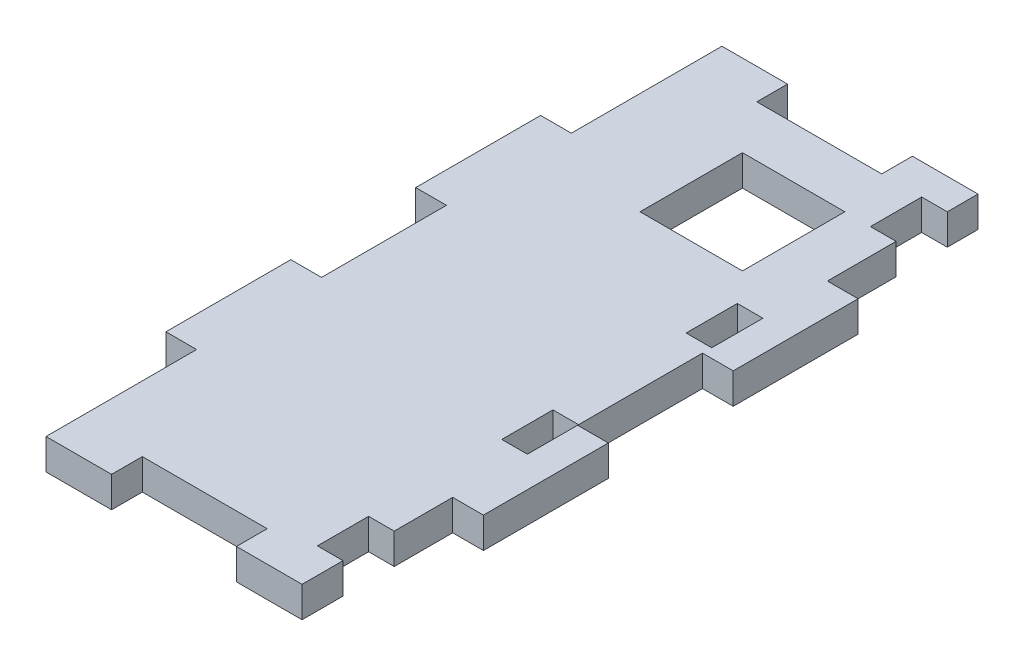
SolidWorks part; units mm, degrees
ref_plane "Front Plane" through (0, 0, 0) normal (0, 0, 1) x (1, 0, 0)
ref_plane "Top Plane" through (0, 0, 0) normal (0, 1, 0) x (1, 0, 0)
ref_plane "Right Plane" through (0, 0, 0) normal (1, 0, 0) x (0, 0, -1)
sketch "Sketch2" plane through (0, 0, 0) normal (0, 1, 0) x (1, 0, 0)
  line L0 (121, 270) -> (121, 240.585)
  line L1 (121, 240.585) -> (115, 240.585)
  line L2 (115, 240.585) -> (115, 216.195)
  line L3 (115, 216.195) -> (121, 216.195)
  line L4 (121, 216.195) -> (121, 191.805)
  line L5 (121, 191.805) -> (115, 191.805)
  line L6 (115, 191.805) -> (115, 167.415)
  line L7 (115, 167.415) -> (121, 167.415)
  line L8 (121, 167.415) -> (121, 143.025)
  line L9 (121, 143.025) -> (121, 138)
  line L10 (121, 138) -> (133.805, 138)
  line L11 (133.805, 138) -> (133.805, 144)
  line L12 (133.805, 144) -> (158.195, 144)
  line L13 (158.195, 144) -> (158.195, 138)
  line L14 (158.195, 138) -> (171, 138)
  line L15 (171, 138) -> (171, 167.415)
  line L16 (171, 167.415) -> (177, 167.415)
  line L17 (177, 167.415) -> (177, 191.805)
  line L18 (177, 191.805) -> (171, 191.805)
  line L19 (171, 191.805) -> (171, 216.195)
  line L20 (171, 216.195) -> (177, 216.195)
  line L21 (177, 216.195) -> (177, 240.585)
  line L22 (177, 240.585) -> (171, 240.585)
  line L23 (171, 240.585) -> (171, 264.975)
  line L24 (171, 264.975) -> (171, 270)
  line L25 (171, 270) -> (158.195, 270)
  line L26 (158.195, 270) -> (158.195, 264)
  line L27 (158.195, 264) -> (133.805, 264)
  line L28 (133.805, 264) -> (133.805, 270)
  line L29 (133.805, 270) -> (121, 270)
extrude "Boss-Extrude1" add sketch "Sketch2" along normal blind 6
sketch "Sketch3" plane through (0, 6, 0) normal (0, 1, 0) x (1, 0, 0)
  line L0 (171, 138) -> (171, 167.415) construction
  line L1 (141, 254) -> (161, 254)
  line L2 (141, 254) -> (141, 234)
  line L3 (141, 234) -> (161, 234)
  line L4 (161, 254) -> (161, 234)
  line L5 (158.195, 264) -> (133.805, 264) construction
  line L6 (171, 228) -> (171, 218)
  line L7 (171, 240.585) -> (171, 270) construction
  line L8 (171, 264) -> (166, 264)
  line L9 (171, 264) -> (171, 254)
  line L10 (171, 254) -> (166, 254)
  line L11 (166, 264) -> (166, 254)
  line L12 (171, 270) -> (158.195, 270) construction
  line L13 (171, 228) -> (166, 228)
  line L14 (166, 228) -> (166, 218)
  line L15 (171, 218) -> (166, 218)
  line L16 (171, 192) -> (171, 182)
  line L17 (171, 192) -> (166, 192)
  line L18 (166, 192) -> (166, 182)
  line L19 (171, 182) -> (166, 182)
  line L20 (171, 156) -> (171, 146)
  line L21 (171, 156) -> (166, 156)
  line L22 (166, 156) -> (166, 146)
  line L23 (171, 146) -> (166, 146)
  dimension "D1" = 20
  dimension "D2" = 20
  dimension "D3" = 10
  dimension "D4" = 10
  dimension "D5" = 6
  dimension "D6" = 10
  dimension "D7" = 5
  dimension "D8" = 4
extrude "Cut-Extrude1" cut sketch "Sketch3" against normal blind 6
